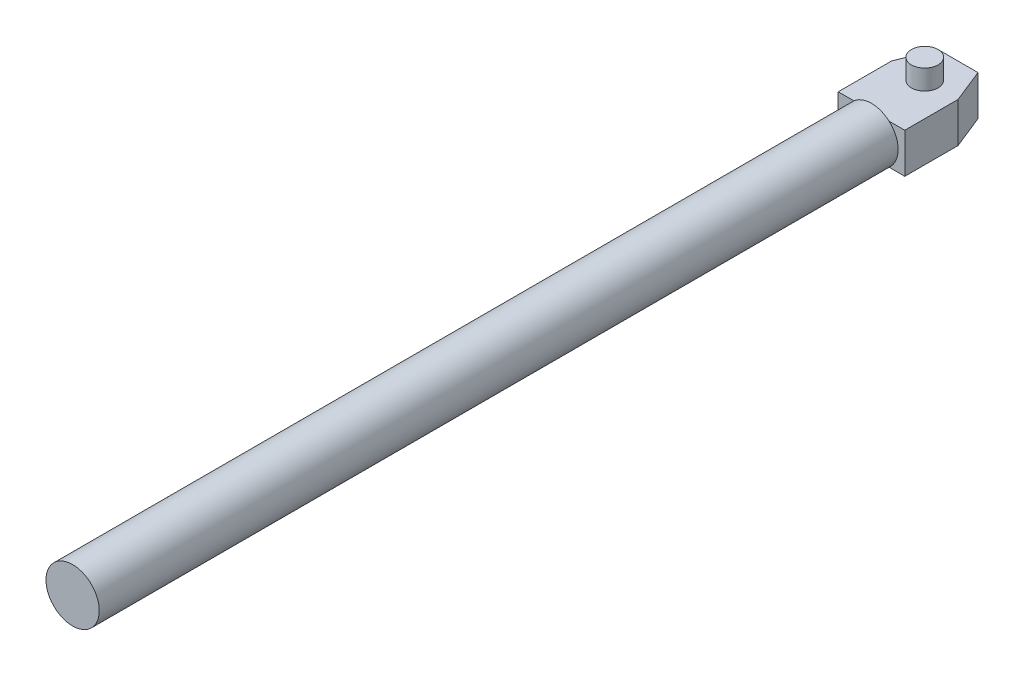
SolidWorks part; units mm, degrees
ref_plane "Front Plane" through (0, 0, 0) normal (0, 0, 1) x (1, 0, 0)
ref_plane "Top Plane" through (0, 0, 0) normal (0, 1, 0) x (1, 0, 0)
ref_plane "Right Plane" through (0, 0, 0) normal (1, 0, 0) x (0, 0, -1)
sketch "Sketch1" plane through (0, 0, 0) normal (0, 0, 1) x (1, 0, 0)
  circle A0 centre (0, 0) radius 20
  dimension "D1" = 40
extrude "Boss-Extrude1" add sketch "Sketch1" along normal blind 600
sketch "Sketch2" plane through (0, 0, 0) normal (0, 1, 0) x (1, 0, 0)
  line L0 (-25, 40) -> (-15, 65)
  line L1 (-25, 0) -> (25, 0)
  line L2 (-25, 0) -> (-25, 40)
  line L3 (-15, 65) -> (15, 65)
  line L4 (25, 0) -> (25, 40)
  line L5 (15, 65) -> (25, 40)
  point P1 (25, 65)
  point P2 (-25, 65)
  dimension "D1" = 50
  dimension "D2" = 65
  dimension "D3" = 25
  dimension "D4" = 10
  dimension "D5" = 10
  dimension "D6" = 25
extrude "Boss-Extrude2" add sketch "Sketch2" along normal mid plane 30
sketch "Sketch3" plane through (0, 0, 0) normal (0, 1, 0) x (1, 0, 0)
  circle A0 centre (0, 40) radius 10
  dimension "D1" = 20
  dimension "D2" = 40
extrude "Boss-Extrude3" add sketch "Sketch3" along normal mid plane 60
